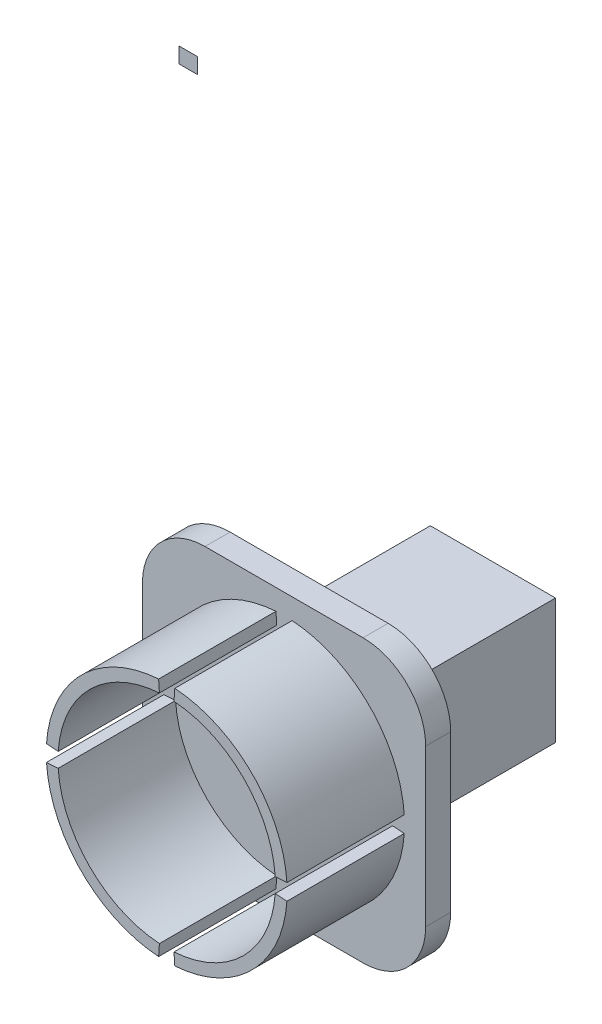
SolidWorks part; units mm, degrees
ref_plane "Front Plane" through (0, 0, 0) normal (0, 0, 1) x (1, 0, 0)
ref_plane "Top Plane" through (0, 0, 0) normal (0, 1, 0) x (1, 0, 0)
ref_plane "Right Plane" through (0, 0, 0) normal (1, 0, 0) x (0, 0, -1)
sketch "Sketch1" plane through (0, 0, 0) normal (0, 0, 1) x (1, 0, 0)
  line L13 (-20.0541, 22.5273) -> (-18.8954, 22.5273)
  line L14 (-20.0541, 22.5273) -> (-20.0541, 21.5306)
  line L15 (-20.0541, 21.5306) -> (-18.8954, 21.5306)
  line L16 (-18.8954, 22.5273) -> (-18.8954, 21.5306)
  point P4 (0, 0)
  point P5 (0, 0)
  point P6 (0, 0)
  point P7 (0, 0)
  point P8 (-17.7331, 20.5156)
  point P9 (-18.8954, 21.5306)
extrude "Boss-Extrude1" add sketch "Sketch1" along normal blind 0.0005
sketch "Sketch2" plane through (0, 0, 0) normal (0, 0, 1) x (1, 0, 0)
  line L1 (-4, 4) -> (4, 4)
  line L2 (-4, 4) -> (-4, -4)
  line L3 (-4, -4) -> (4, -4)
  line L4 (4, 4) -> (4, -4)
  line L6 (-2.5794, 1.43) -> (2.5794, 1.43)
  line L7 (2.5802, -1.4285) -> (-2.5785, -1.4315)
  arc A1 (-2.5794, 1.43) -> (-2.5785, -1.4315) centre (0, 0) ccw
  arc A2 (2.5794, 1.43) -> (2.5802, -1.4285) centre (0, 0) cw
  dimension "D3" = 1.43
  dimension "D1" = 8
  dimension "D2" = 4
  dimension "D4" = 1.43
extrude "Boss-Extrude2" add sketch "Sketch2" along normal blind 11.7499
sketch "Sketch3" plane through (0, 0, 11.7499) normal (0, 0, 1) x (1, 0, 0)
  line L1 (-5.05, 9.0001) -> (5.05, 9.0001)
  line L2 (-9.05, 5.0001) -> (-9.05, -5.0001)
  line L3 (-5.05, -9.0001) -> (5.05, -9.0001)
  line L4 (9.05, 5.0001) -> (9.05, -5.0001)
  line L5 (-9.05, 9.0001) -> (9.05, -9.0001) construction
  line L6 (-9.05, -9.0001) -> (9.05, 9.0001) construction
  arc A0 (-9.05, -5.0001) -> (-5.05, -9.0001) centre (-5.05, -5.0001) ccw
  arc A1 (5.05, -9.0001) -> (9.05, -5.0001) centre (5.05, -5.0001) ccw
  arc A2 (5.05, 9.0001) -> (9.05, 5.0001) centre (5.05, 5.0001) cw
  arc A3 (-5.05, 9.0001) -> (-9.05, 5.0001) centre (-5.05, 5.0001) ccw
  point P0 (0, 0)
  dimension "D2" = 4
  dimension "D1" = 9.05
extrude "Boss-Extrude3" add sketch "Sketch3" along normal blind 1.6
sketch "Sketch4" plane through (0, 0, 13.3499) normal (0, 0, 1) x (1, 0, 0)
  circle A1 centre (0, 0) radius 7.7
  dimension "D2" = 15.4
extrude "Boss-Extrude4" add sketch "Sketch4" along normal blind 7.5
sketch "Sketch5" plane through (0, 0, 13.3499) normal (0, 0, 1) x (1, 0, 0)
  circle A0 centre (0, 0) radius 6.95
  dimension "D1" = 13.9
extrude "Cut-Extrude1" cut sketch "Sketch5" along normal blind 7.5
sketch "Sketch11" plane through (0, 0, 13.3499) normal (0, 0, 1) x (1, 0, 0)
  line L4 (0, 8.1838) -> (-0.55, 8.1838)
  line L5 (-0.55, 8.1838) -> (0, 0)
  line L6 (0, 8.1838) -> (0.55, 8.1838)
  line L7 (0.55, 8.1838) -> (0, 0)
  dimension "D1" = 0.55
  dimension "D2" = 0.55
extrude "Cut-Extrude2" cut sketch "Sketch11" along normal blind 7.5
pattern_circular "CirPattern1" count 4 over 360 about axis through (0, 0, 20.8499) along (0, 0, -1) of "Cut-Extrude2"
